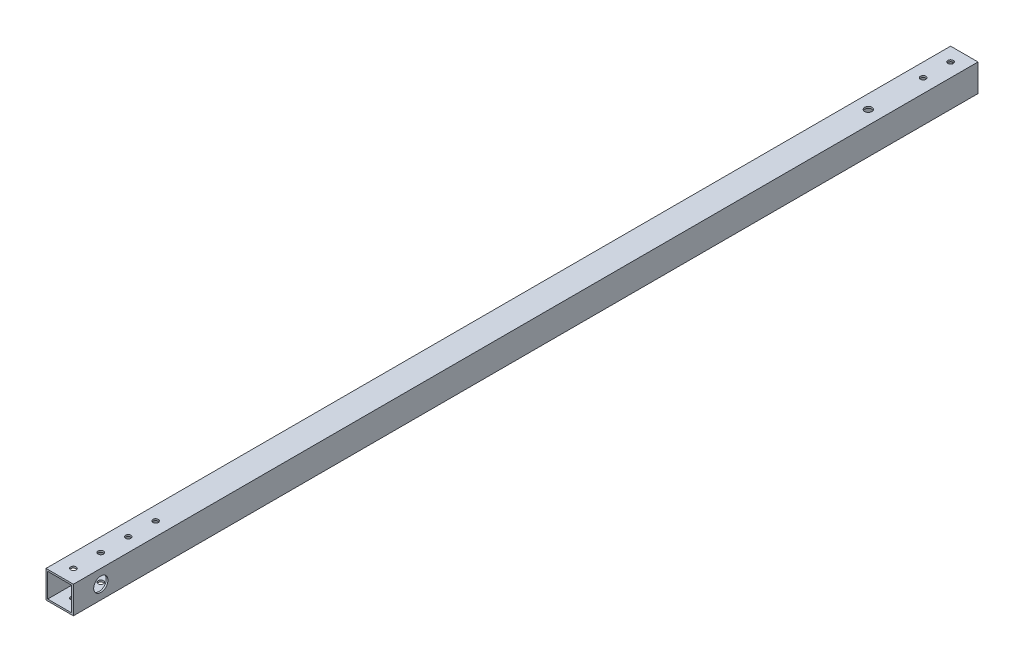
SolidWorks part; units mm, degrees
ref_plane "Front Plane" through (0, 0, 0) normal (0, 0, 1) x (1, 0, 0)
ref_plane "Top Plane" through (0, 0, 0) normal (0, 1, 0) x (1, 0, 0)
ref_plane "Right Plane" through (0, 0, 0) normal (1, 0, 0) x (0, 0, -1)
sketch "Sketch1" plane through (0, 0, 0) normal (0, 0, 1) x (1, 0, 0)
  line L1 (0, 0) -> (25.4, 0)
  line L2 (0, 0) -> (0, 25.4)
  line L3 (0, 25.4) -> (25.4, 25.4)
  line L4 (25.4, 0) -> (25.4, 25.4)
  line L5 (1.5875, 1.5875) -> (23.8125, 1.5875)
  line L6 (1.5875, 1.5875) -> (1.5875, 23.8125)
  line L7 (1.5875, 23.8125) -> (23.8125, 23.8125)
  line L8 (23.8125, 1.5875) -> (23.8125, 23.8125)
  dimension "D1" = 25.4
  dimension "D2" = 1.5875
  dimension "D3" = 1.5875
  dimension "D4" = 1.5875
  dimension "D5" = 1.5875
extrude "Boss-Extrude1" add sketch "Sketch1" along normal blind 838.2
sketch "Sketch3" plane through (0, 25.4, 0) normal (0, 1, 0) x (1, 0, 0)
  line L1 (25.4, -838.2) -> (25.4, 0) construction
  line L2 (25.4, 0) -> (0, 0) construction
  line L3 (25.4, -838.2) -> (0, -838.2) construction
  circle A1 centre (12.7, -12.7) radius 2.54
  circle A4 centre (12.7, -825.5) radius 2.54
  circle A5 centre (12.7, -38.1) radius 2.54
  circle A7 centre (12.7, -88.9) radius 3.429
  circle A8 centre (12.7, -800.1) radius 2.54
  circle A9 centre (12.7, -774.7) radius 2.54
  circle A10 centre (12.7, -749.3) radius 2.54
  dimension "D3" = 12.7
  dimension "D6" = 6.858
  dimension "D1" = 5.08
  dimension "D2" = 12.7
  dimension "D4" = 12.7
  dimension "D5" = 4
  dimension "D7" = 25.4
  dimension "D8" = 50.8
extrude "Cut-Extrude2" cut sketch "Sketch3" against normal through all
sketch "Sketch4" plane through (25.4, 0, 0) normal (1, 0, 0) x (0, 0, -1)
  line L0 (-838.2, 0) -> (0, 0) construction
  line L1 (-838.2, 0) -> (-838.2, 25.4) construction
  circle A0 centre (-812.8, 12.7) radius 6.604
  dimension "D3" = 13.208
  dimension "D1" = 12.7
  dimension "D2" = 25.4
extrude "Cut-Extrude3" cut sketch "Sketch4" against normal through all both and the other way through all
